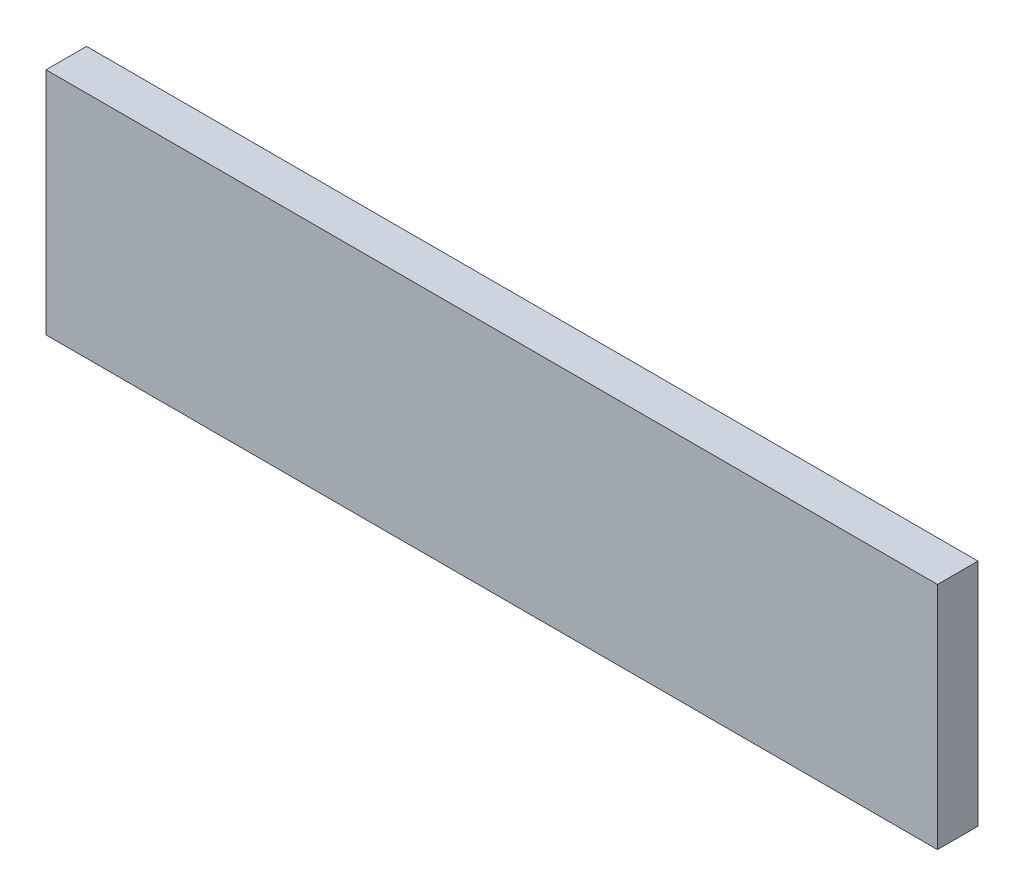
SolidWorks part; units mm, degrees
ref_plane "Plano frontal" through (0, 0, 0) normal (0, 0, 1) x (1, 0, 0)
ref_plane "Plano superior" through (0, 0, 0) normal (0, 1, 0) x (1, 0, 0)
ref_plane "Plano direito" through (0, 0, 0) normal (1, 0, 0) x (0, 0, -1)
sketch "Esboço1" plane through (0, 0, 0) normal (0, 0, 1) x (1, 0, 0)
  line L1 (-165, 42.5) -> (165, 42.5)
  line L2 (-165, 42.5) -> (-165, -42.5)
  line L3 (-165, -42.5) -> (165, -42.5)
  line L4 (165, 42.5) -> (165, -42.5)
  line L5 (-165, 42.5) -> (165, -42.5) construction
  line L6 (-165, -42.5) -> (165, 42.5) construction
  point P0 (0, 0)
  dimension "D1" = 330
  dimension "D2" = 85
extrude "Ressalto-extrusão1" add sketch "Esboço1" along normal blind 15
